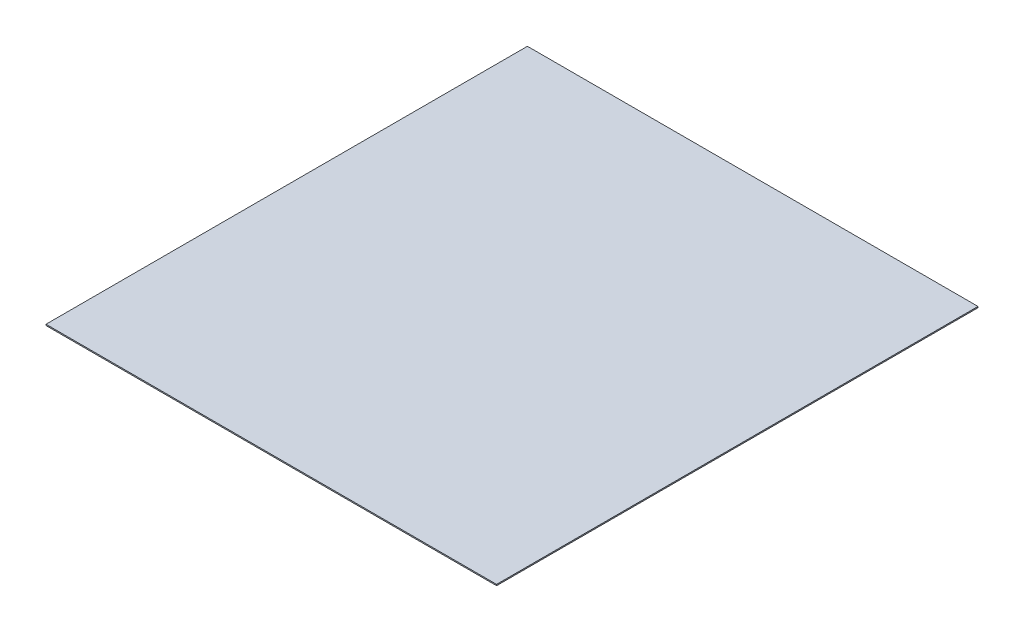
SolidWorks part; units mm, degrees
material "6061 Alloy"
ref_plane "Front Plane" through (0, 0, 0) normal (0, 0, 1) x (1, 0, 0)
ref_plane "Top Plane" through (0, 0, 0) normal (0, 1, 0) x (1, 0, 0)
ref_plane "Right Plane" through (0, 0, 0) normal (1, 0, 0) x (0, 0, -1)
sketch "Sketch2" plane through (0, 0, 0) normal (0, 1, 0) x (1, 0, 0)
  line L1 (-95, 101.5) -> (95, 101.5)
  line L2 (-95, 101.5) -> (-95, -101.5)
  line L3 (-95, -101.5) -> (95, -101.5)
  line L4 (95, 101.5) -> (95, -101.5)
  line L5 (-95, 101.5) -> (95, -101.5) construction
  line L6 (-95, -101.5) -> (95, 101.5) construction
  point P0 (0, 0)
  dimension "D1" = 190
  dimension "D2" = 203
extrude "Boss-Extrude2" add sketch "Sketch2" along normal blind 0.5
